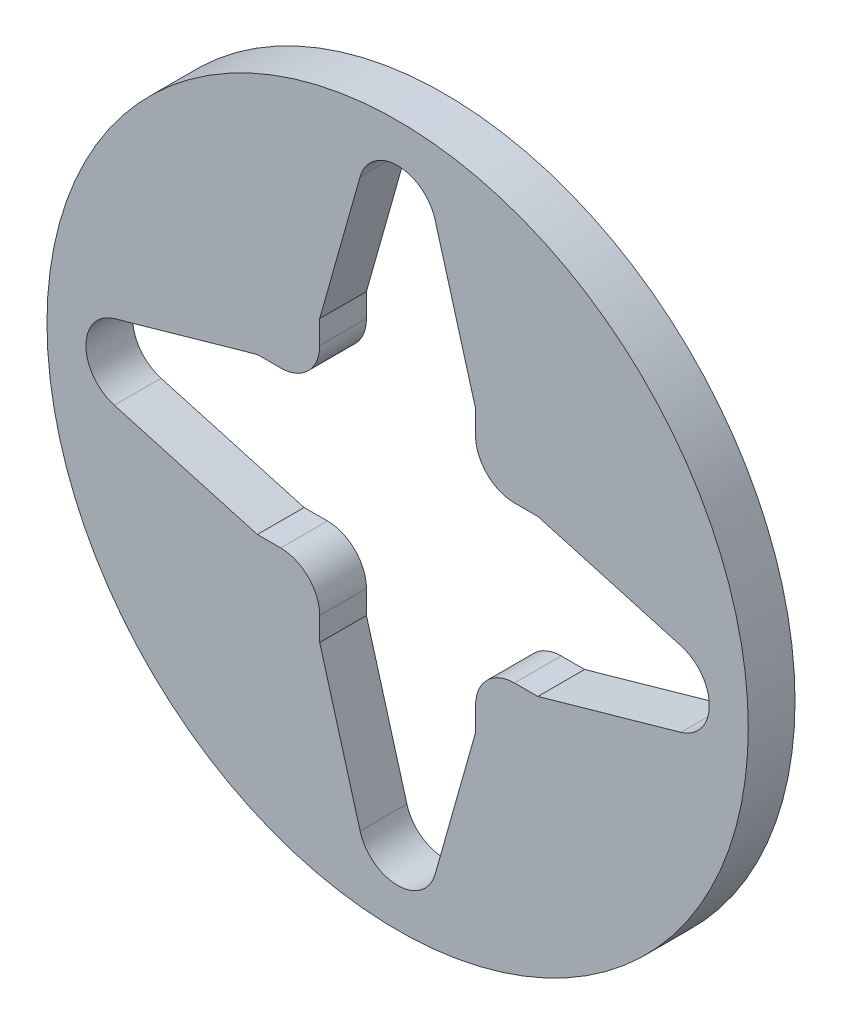
SolidWorks part; units mm, degrees
ref_plane "Front Plane" through (0, 0, 0) normal (0, 0, 1) x (1, 0, 0)
ref_plane "Top Plane" through (0, 0, 0) normal (0, 1, 0) x (1, 0, 0)
ref_plane "Right Plane" through (0, 0, 0) normal (1, 0, 0) x (0, 0, -1)
sketch "Sketch1" plane through (0, 0, 0) normal (0, 0, 1) x (1, 0, 0)
  line L0 (-5, 5) -> (-5, 9)
  line L8 (5, -5) -> (-5, -5)
  line L9 (5, -5) -> (5, 5)
  line L10 (5, 5) -> (-5, 5)
  line L11 (-5, -5) -> (-5, 5)
  line L12 (5, -5) -> (-5, 5) construction
  line L13 (5, 5) -> (-5, -5) construction
  line L14 (-5, 9) -> (-2.4058, 18.1799)
  line L15 (0, -55) -> (0, 55) construction
  line L16 (9, 5) -> (18.1799, 2.4058)
  line L17 (5, 5) -> (5, 9)
  line L18 (55, 0) -> (-55, 0) construction
  line L19 (5, -5) -> (5, -9)
  line L20 (-5, -9) -> (-2.4058, -18.1799)
  line L21 (5, -9) -> (2.4058, -18.1799)
  line L22 (-5, -5) -> (-5, -9)
  line L23 (5, -5) -> (9, -5)
  line L24 (9, -5) -> (18.1799, -2.4058)
  line L25 (-9, -5) -> (-18.1799, -2.4058)
  line L26 (5, 5) -> (9, 5)
  line L27 (-5, -5) -> (-9, -5)
  line L28 (-9, 5) -> (-18.1799, 2.4058)
  line L29 (5, 9) -> (2.4058, 18.1799)
  line L30 (-5, 5) -> (-9, 5)
  line L31 (0, 22.5) -> (-22.5, 0)
  line L32 (-22.5, 0) -> (-22.5, 22.5)
  line L33 (-22.5, 22.5) -> (0, 22.5)
  line L34 (-27.0416, 0) -> (-22.5, 0)
  line L35 (-22.5, 22.5) -> (-79.5, 22.5)
  line L36 (-22.5, 22.5) -> (-22.5, 0)
  line L37 (-22.5, 0) -> (-79.5, 0)
  line L38 (-79.5, 22.5) -> (-79.5, 0)
  line L41 (-22.5, 0) -> (-22.125, -4.0909)
  circle A0 centre (0, 0) radius 22.5
  circle A1 centre (0, 17.5) radius 2.5
  circle A2 centre (0, -17.5) radius 2.5
  circle A3 centre (17.5, 0) radius 2.5
  circle A4 centre (-17.5, 0) radius 2.5
  circle A5 centre (-7.5, 7.5) radius 2.5
  circle A6 centre (-7.5, -7.5) radius 2.5
  circle A7 centre (7.5, 7.5) radius 2.5
  circle A8 centre (7.5, -7.5) radius 2.5
  arc A9 (-27.0416, 0) -> (-22.125, -4.0909) centre (-27.0416, -5) cw
  dimension "D1" = 45
  dimension "D3" = 5
  dimension "D5" = 12.5
  dimension "D6" = 5
  dimension "D9" = 5
  dimension "D11" = 5
  dimension "D2" = 10
  dimension "D4" = 4
  dimension "D7" = 4
  dimension "D8" = 12.5
  dimension "D10" = 57
extrude "Boss-Extrude1" add sketch "Sketch1" along normal blind 3
sketch "Sketch3" [suppressed] plane through (0, 0, 3) normal (0, 0, 1) x (1, 0, 0)
  circle A0 centre (0, 0) radius 5
  circle A1 centre (0, 0) radius 22.5
  arc A2 (-22.125, -4.0909) -> (0, 22.5) centre (0, 0) ccw construction
  dimension "D1" = 10
extrude "Boss-Extrude2" [suppressed] add sketch "Sketch3" against normal up to surface (3 mm away)
sketch "Sketch4" plane through (0, 0, 3) normal (0, 0, 1) x (1, 0, 0)
  line L0 (-79.5, 22.5) -> (0, 22.5) construction
  line L1 (-79.5, 22.5) -> (-79.5, 0) construction
  line L2 (-27.0416, 0) -> (-79.5, 0) construction
  line L3 (-79.5, 22.5) -> (0, 22.5)
  line L4 (-79.5, 22.5) -> (-79.5, 0)
  line L5 (-27.0416, 0) -> (-79.5, 0)
  arc A0 (0, 22.5) -> (-22.125, -4.0909) centre (0, 0) ccw
  arc A1 (-22.125, -4.0909) -> (0, 22.5) centre (0, 0) ccw construction
  arc A2 (-22.125, -4.0909) -> (-27.0416, 0) centre (-27.0416, -5) ccw construction
  arc A3 (-22.125, -4.0909) -> (-27.0416, 0) centre (-27.0416, -5) ccw
extrude "Cut-Extrude1" cut sketch "Sketch4" against normal through all
